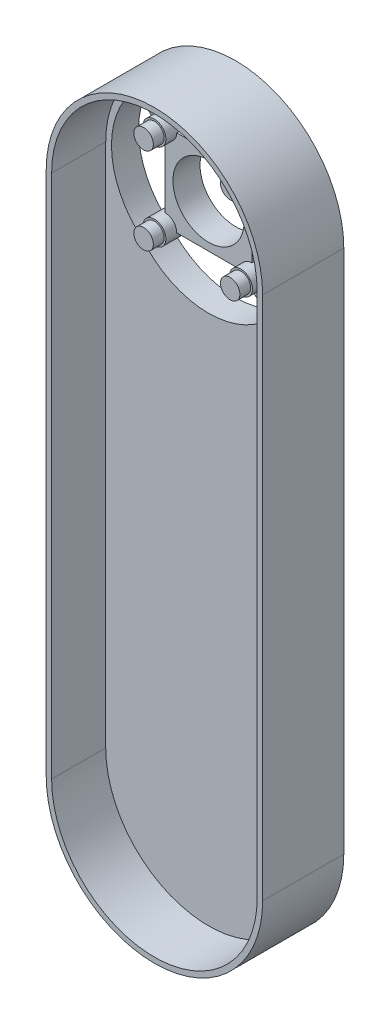
SolidWorks part; units mm, degrees
material "PLA"
ref_plane "Front Plane" through (0, 0, 0) normal (0, 0, 1) x (1, 0, 0)
ref_plane "Top Plane" through (0, 0, 0) normal (0, 1, 0) x (1, 0, 0)
ref_plane "Right Plane" through (0, 0, 0) normal (1, 0, 0) x (0, 0, -1)
sketch "Sketch2" plane through (0, 0, 0) normal (0, 0, 1) x (1, 0, 0)
  line L0 (-20, 0) -> (-20, -97)
  line L1 (20, 0) -> (20, -97)
  circle A0 centre (0, 0) radius 6.575
  arc A1 (20, 0) -> (-20, 0) centre (0, 0) ccw
  arc A2 (-20, -97) -> (20, -97) centre (0, -97) ccw
  dimension "D1" = 13.15
  dimension "D2" = 20
  dimension "D3" = 20
  dimension "D4" = 97
extrude "Boss-Extrude1" add sketch "Sketch2" along normal blind 5
sketch "Sketch3" plane through (0, 0, 5) normal (0, 0, 1) x (1, 0, 0)
  circle A0 centre (0, -97) radius 4.5
  dimension "D1" = 9
sketch "Sketch4" plane through (0, 0, 5) normal (0, 0, 1) x (1, 0, 0)
  circle A0 centre (-8, 8) radius 2.125
  circle A1 centre (8, 8) radius 2.125
  circle A2 centre (8, -8) radius 2.125
  circle A3 centre (-8, -8) radius 2.125
  dimension "D6" = 4.25
  dimension "D1" = 16
  dimension "D2" = 16
  dimension "D3" = 16
  dimension "D4" = 8
  dimension "D5" = 8
extrude "Boss-Extrude3" add sketch "Sketch4" along normal blind 2
sketch "Sketch5" plane through (0, 0, 7) normal (0, 0, 1) x (1, 0, 0)
  circle A0 centre (-8, 8) radius 1.8
  circle A1 centre (8, 8) radius 1.8
  circle A2 centre (8, -8) radius 1.8
  circle A3 centre (-8, -8) radius 1.8
  dimension "D1" = 3.6
extrude "Boss-Extrude4" add sketch "Sketch5" along normal blind 2
sketch "Sketch6" plane through (0, 0, 5) normal (0, 0, 1) x (1, 0, 0)
  line L0 (20, -97) -> (20, 0) construction
  line L1 (-20, 0) -> (-20, -97) construction
  line L2 (20, -97) -> (20, 0)
  line L3 (-20, 0) -> (-20, -97)
  line L4 (-19, 0) -> (-19, -97)
  line L5 (19, -97) -> (19, 0)
  arc A0 (-20, -97) -> (20, -97) centre (0, -97) ccw construction
  arc A1 (20, 0) -> (-20, 0) centre (0, 0) ccw construction
  arc A2 (-20, -97) -> (20, -97) centre (0, -97) ccw
  arc A3 (20, 0) -> (-20, 0) centre (0, 0) ccw
  arc A4 (-19, -97) -> (19, -97) centre (0, -97) ccw
  arc A5 (19, 0) -> (-19, 0) centre (0, 0) ccw
  dimension "D1" = 1
extrude "Boss-Extrude5" add sketch "Sketch6" along normal blind 10
sketch "Sketch7" plane through (0, 0, 5) normal (0, 0, 1) x (1, 0, 0)
  line L0 (-10.125, 8) -> (-10.125, -8)
  line L1 (-8, -10.125) -> (8, -10.125)
  line L2 (10.125, -8) -> (10.125, 8)
  line L3 (8, 10.125) -> (-8, 10.125)
  line L4 (-5.875, 8) -> (5.875, 8)
  line L5 (8, 5.875) -> (8, -5.875)
  line L6 (5.875, -8) -> (-5.875, -8)
  line L7 (-8, 5.875) -> (-8, -5.875)
  circle A0 centre (-8, 8) radius 2.125 construction
  circle A1 centre (-8, 8) radius 2.125 construction
  circle A2 centre (-8, -8) radius 2.125 construction
  circle A3 centre (-8, -8) radius 2.125 construction
  circle A4 centre (8, -8) radius 2.125 construction
  circle A5 centre (8, -8) radius 2.125 construction
  circle A6 centre (8, 8) radius 2.125 construction
  circle A7 centre (8, 8) radius 2.125 construction
  arc A8 (-8, -10.125) -> (-5.875, -8) centre (-8, -8) ccw
  arc A9 (10.125, -8) -> (8, -5.875) centre (8, -8) ccw
  arc A10 (8, 10.125) -> (5.875, 8) centre (8, 8) ccw
  arc A11 (-10.125, 8) -> (-8, 5.875) centre (-8, 8) ccw
  arc A12 (-5.875, 8) -> (-8, 10.125) centre (-8, 8) ccw
  arc A13 (8, 5.875) -> (10.125, 8) centre (8, 8) ccw
  arc A14 (5.875, -8) -> (8, -10.125) centre (8, -8) ccw
  arc A15 (-8, -5.875) -> (-10.125, -8) centre (-8, -8) ccw
  dimension "D1" = 16
  dimension "D2" = 11.75
extrude "Cut-Extrude1" cut sketch "Sketch7" against normal blind 10
sketch "Sketch9" plane through (0, 0, 15) normal (0, 0, 1) x (1, 0, 0)
  line L0 (-20, 0) -> (-20, -97) construction
  line L1 (20, -97) -> (20, 0) construction
  line L2 (-20, 0) -> (-20, -97)
  line L3 (20, -97) -> (20, 0)
  arc A1 (20, 0) -> (-20, 0) centre (0, 0) ccw construction
  arc A3 (20, 0) -> (-20, 0) centre (0, 0) ccw
  arc A5 (19, -97) -> (-19, -97) centre (0, -97) ccw
  arc A6 (-20, -97) -> (20, -97) centre (0, -97) ccw construction
  arc A7 (-19, -97) -> (19, -97) centre (0, -97) ccw construction
  arc A8 (-20, -97) -> (20, -97) centre (0, -97) ccw
  arc A9 (-19, -97) -> (19, -97) centre (0, -97) ccw
sketch "Sketch10" plane through (0, 0, 0) normal (0, 0, -1) x (-1, 0, 0)
  line L0 (-8, 10.125) -> (-11.182, 13.307)
  line L1 (-8, 10.125) -> (8, 10.125) construction
  line L2 (-10.125, 8) -> (-13.307, 11.182)
  line L3 (8, 10.125) -> (11.182, 13.307)
  line L4 (10.125, 8) -> (13.307, 11.182)
  line L5 (10.125, -8) -> (13.307, -11.182)
  line L6 (8, -10.125) -> (11.182, -13.307)
  line L7 (-8, -10.125) -> (-11.182, -13.307)
  line L8 (-10.125, -8) -> (-13.307, -11.182)
  line L9 (-8, 10.125) -> (8, 10.125)
  line L10 (-10.125, -8) -> (-10.125, 8) construction
  line L11 (-10.125, -8) -> (-10.125, 8)
  line L12 (10.125, 8) -> (10.125, -8) construction
  line L13 (10.125, 8) -> (10.125, -8)
  line L14 (8, -10.125) -> (-8, -10.125) construction
  line L15 (8, -10.125) -> (-8, -10.125)
  arc A2 (-11.182, 13.307) -> (11.182, 13.307) centre (0, 2.125) cw
  arc A3 (13.307, 11.182) -> (13.307, -11.182) centre (2.125, 0) cw
  arc A4 (11.182, -13.307) -> (-11.182, -13.307) centre (0, -2.125) cw
  arc A5 (-13.307, -11.182) -> (-13.307, 11.182) centre (-2.125, 0) cw
  dimension "D2" = 15.8137
  dimension "D1" = 4.5
  dimension "D3" = 11.182
  dimension "D4" = 11.182
  dimension "D5" = 11.182
  dimension "D6" = 11.182
  dimension "D7" = 11.182
  dimension "D8" = 11.182
  dimension "D9" = 11.182
  dimension "D10" = 11.182
extrude "Cut-Extrude2" cut sketch "Sketch10" against normal blind 10
